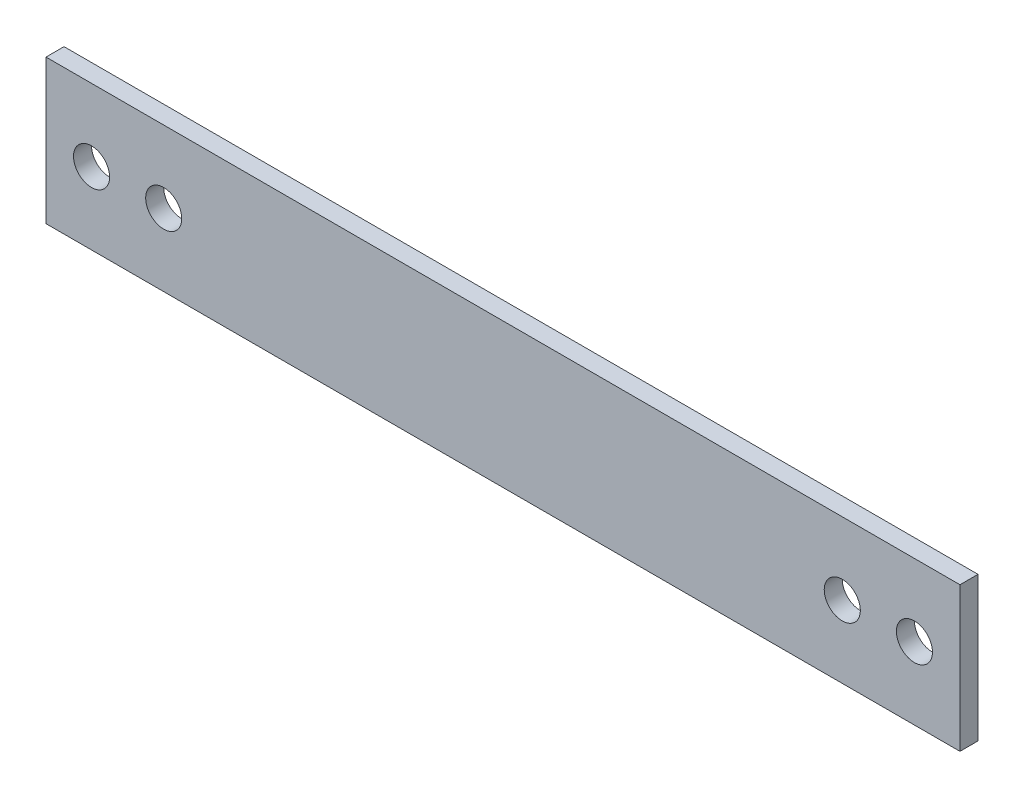
SolidWorks part; units mm, degrees
ref_plane "Front Plane" through (0, 0, 0) normal (0, 0, 1) x (1, 0, 0)
ref_plane "Top Plane" through (0, 0, 0) normal (0, 1, 0) x (1, 0, 0)
ref_plane "Right Plane" through (0, 0, 0) normal (1, 0, 0) x (0, 0, -1)
sketch "Sketch1" plane through (0, 0, 0) normal (0, 0, 1) x (1, 0, 0)
  line L1 (-120.65, -19.05) -> (120.65, -19.05)
  line L2 (-120.65, -19.05) -> (-120.65, 19.05)
  line L3 (-120.65, 19.05) -> (120.65, 19.05)
  line L4 (120.65, -19.05) -> (120.65, 19.05)
  line L5 (0, 19.05) -> (0, -19.05) construction
  line L6 (-120.65, 0) -> (120.65, 0) construction
  circle A0 centre (-108.6255, 0) radius 4.7625
  circle A1 centre (-89.5755, 0) radius 4.7625
  circle A2 centre (89.5755, 0) radius 4.7625
  circle A3 centre (108.6255, 0) radius 4.7625
  point P0 (0, 0)
  dimension "D3" = 9.525
  dimension "D1" = 38.1
  dimension "D2" = 241.3
  dimension "D4" = 19.05
extrude "Boss-Extrude1" add sketch "Sketch1" along normal blind 4.7625
